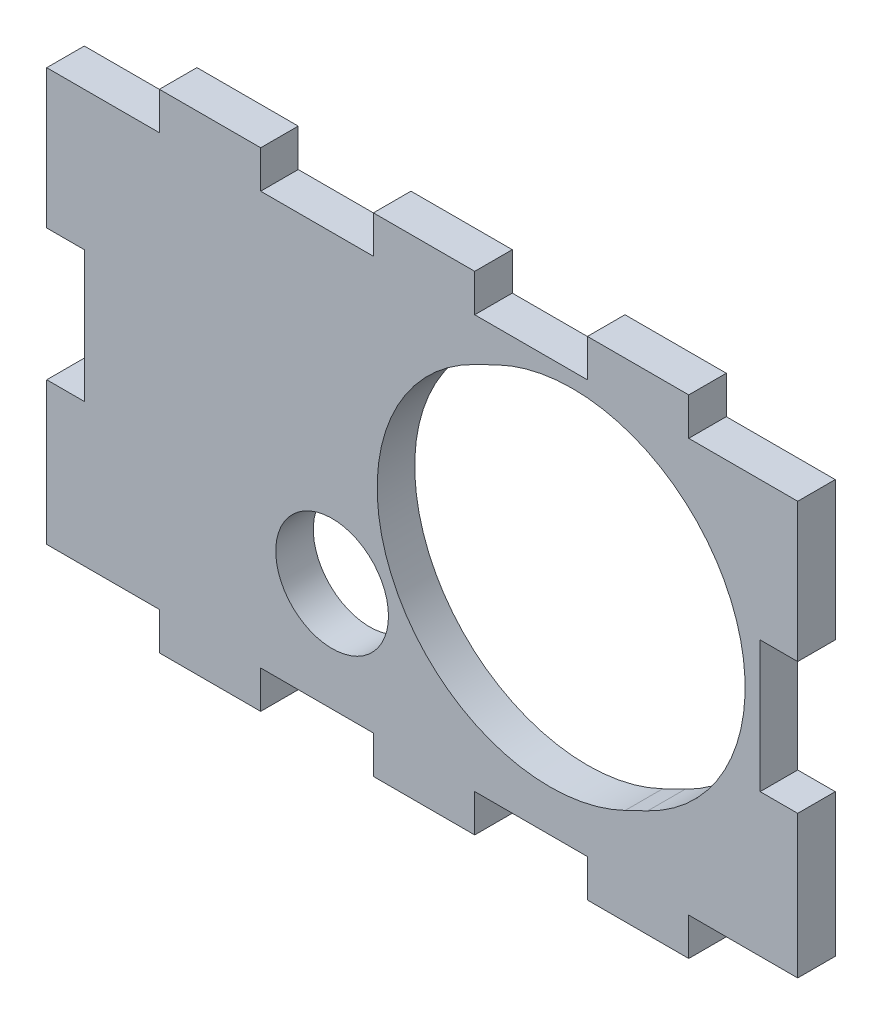
SolidWorks part; units mm, degrees
material "Acrylique (impact moyen-haut)"
ref_plane "Plan de face" through (0, 0, 0) normal (0, 0, 1) x (1, 0, 0)
ref_plane "Plan de dessus" through (0, 0, 0) normal (0, 1, 0) x (1, 0, 0)
ref_plane "Plan de droite" through (0, 0, 0) normal (1, 0, 0) x (0, 0, -1)
sketch "Esquisse1" plane through (0, 0, 0) normal (0, 0, 1) x (1, 0, 0)
  line L1 (50, -32.5) -> (-50, -32.5)
  line L2 (50, -32.5) -> (50, 32.5)
  line L3 (50, 32.5) -> (-50, 32.5)
  line L4 (-50, -32.5) -> (-50, 32.5)
  line L5 (50, -32.5) -> (-50, 32.5) construction
  line L6 (50, 32.5) -> (-50, -32.5) construction
  point P0 (0, 0)
  dimension "D1" = 100
  dimension "D2" = 65
extrude "Boss.-Extru.1" add sketch "Esquisse1" along normal blind 5
sketch "Esquisse2" plane through (0, 0, 5) normal (0, 0, 1) x (1, 0, 0)
  line L0 (50, 32.5) -> (-50, 32.5) construction
  line L1 (-50, 32.5) -> (-50, -32.5) construction
  line L2 (50, -32.5) -> (50, 32.5) construction
  line L3 (-35, 32.5) -> (-50, 32.5)
  line L4 (-35, 32.5) -> (-35, 27.49)
  line L5 (-35, 27.49) -> (-50, 27.49)
  line L6 (-50, 32.5) -> (-50, 27.49)
  line L7 (-21.51, 32.5) -> (-6.5, 32.5)
  line L8 (-21.51, 32.5) -> (-21.51, 27.49)
  line L9 (-21.51, 27.49) -> (-6.5, 27.49)
  line L10 (-6.5, 32.5) -> (-6.5, 27.49)
  line L11 (6.99, 32.5) -> (22, 32.5)
  line L12 (6.99, 32.5) -> (6.99, 27.49)
  line L13 (6.99, 27.49) -> (22, 27.49)
  line L14 (22, 32.5) -> (22, 27.49)
  line L15 (35.49, 32.5) -> (50, 32.5)
  line L16 (35.49, 32.5) -> (35.49, 27.49)
  line L17 (35.49, 27.49) -> (50, 27.49)
  line L18 (50, 32.5) -> (50, 27.49)
  line L19 (0, 32.5) -> (0, -35.188) construction
  line L20 (-50, 9) -> (-45, 9)
  line L21 (-50, 9) -> (-50, -8.5)
  line L22 (-50, -8.5) -> (-45, -8.5)
  line L23 (-45, 9) -> (-45, -8.5)
  line L24 (45, 9) -> (45, -8.5)
  line L25 (50, -8.5) -> (45, -8.5)
  line L26 (50, 9) -> (50, -8.5)
  line L27 (50, 9) -> (45, 9)
  line L28 (50.7693, 0) -> (-61.67, 0) construction
  line L29 (50, -32.5) -> (50, -27.49)
  line L30 (35.49, -27.49) -> (50, -27.49)
  line L31 (35.49, -32.5) -> (35.49, -27.49)
  line L32 (35.49, -32.5) -> (50, -32.5)
  line L33 (22, -32.5) -> (22, -27.49)
  line L34 (6.99, -27.49) -> (22, -27.49)
  line L35 (6.99, -32.5) -> (6.99, -27.49)
  line L36 (6.99, -32.5) -> (22, -32.5)
  line L37 (-6.5, -32.5) -> (-6.5, -27.49)
  line L38 (-21.51, -27.49) -> (-6.5, -27.49)
  line L39 (-21.51, -32.5) -> (-21.51, -27.49)
  line L40 (-21.51, -32.5) -> (-6.5, -32.5)
  line L41 (-50, -32.5) -> (-50, -27.49)
  line L42 (-35, -27.49) -> (-50, -27.49)
  line L43 (-35, -32.5) -> (-35, -27.49)
  line L44 (-35, -32.5) -> (-50, -32.5)
  point P0 (-35, 32.5)
  point P1 (-21.51, 32.5)
  point P6 (6.99, 32.5)
  point P8 (35.49, 32.5)
  point P9 (-50, 9)
  point P10 (-50, -8.5)
  point P13 (-50, 27.49)
  dimension "D1" = 15
  dimension "D2" = 13.49
  dimension "D3" = 13.49
  dimension "D4" = 13.49
  dimension "D5" = 43.5
  dimension "D6" = 72
  dimension "D7" = 23.5
  dimension "D8" = 17.5
  dimension "D9" = 5.01
  dimension "D10" = 5
  dimension "D11" = 5.01
  dimension "D12" = 5.01
  dimension "D13" = 5.01
extrude "Enlèv. mat.-Extru.1" cut sketch "Esquisse2" against normal blind 5
sketch "Esquisse3" plane through (0, 0, 5) normal (0, 0, 1) x (1, 0, 0)
  line L0 (50, 9) -> (50, 27.49) construction
  line L1 (22, -32.5) -> (35.49, -32.5) construction
  line L2 (-50, -8.5) -> (-50, -27.49) construction
  line L3 (-6.5, -32.5) -> (6.99, -32.5) construction
  line L4 (20, 2.5) -> (-12, -13) construction
  line L6 (50, -27.49) -> (50, -8.5) construction
  line L7 (20, 2.5) -> (8.9868, 25.2369) construction
  line L8 (6.9736, 21.7464) -> (9.9736, 23.1996)
  line L9 (27.0264, -19.6527) -> (30.0264, -18.1996)
  line L10 (20, 2.5) -> (33.3113, -24.9813) construction
  arc A0 (6.9736, 21.7464) -> (27.0264, -19.6527) centre (17, 1.0469) ccw
  circle A1 centre (-12, -13) radius 7.505
  arc A2 (9.9736, 23.1996) -> (30.0264, -18.1996) centre (20, 2.5) cw
  point P19 (-5.2456, -9.7284)
  point P20 (-2.7996, -8.5436)
  dimension "D3" = 23
  dimension "D4" = 15.01
  dimension "D9" = 23
  dimension "D1" = 30
  dimension "D2" = 35
  dimension "D5" = 38
  dimension "D6" = 19.5
  dimension "D7" = 33.5469
  dimension "D8" = 33
  dimension "D10" = 3
extrude "Enlèv. mat.-Extru.2" cut sketch "Esquisse3" against normal blind 10
